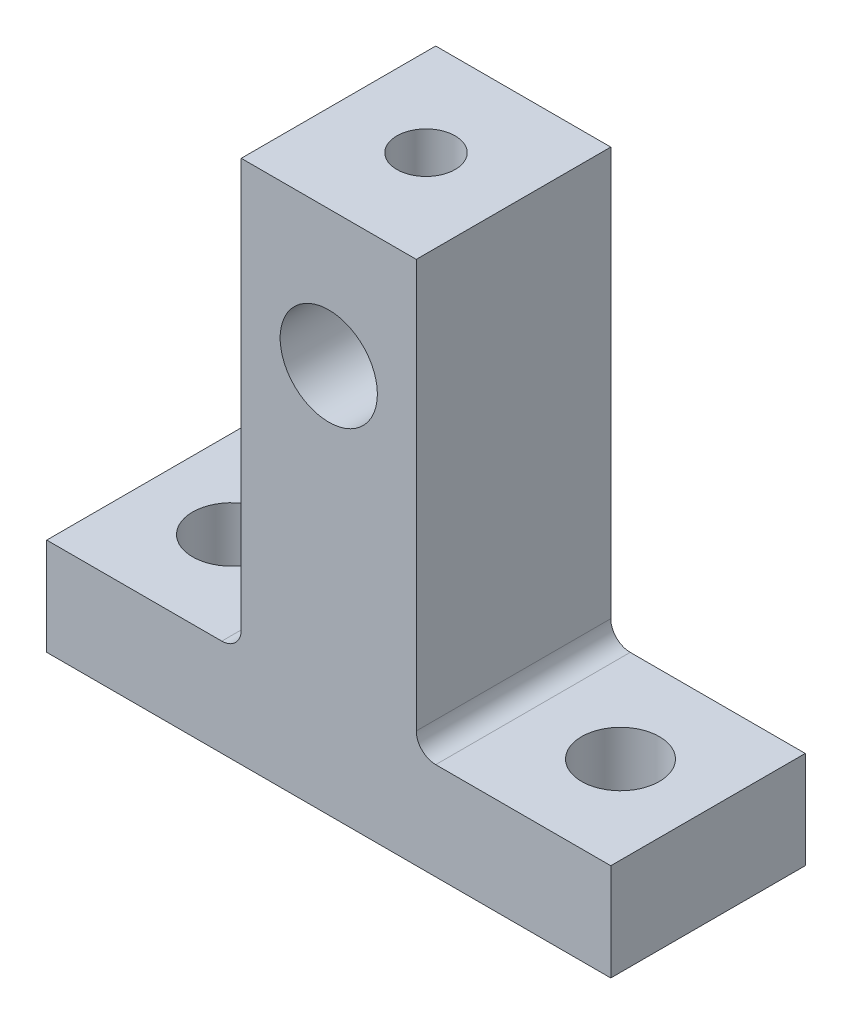
SolidWorks part; units mm, degrees
ref_plane "Front Plane" through (0, 0, 0) normal (0, 0, 1) x (1, 0, 0)
ref_plane "Top Plane" through (0, 0, 0) normal (0, 1, 0) x (1, 0, 0)
ref_plane "Right Plane" through (0, 0, 0) normal (1, 0, 0) x (0, 0, -1)
sketch "Sketch1" plane through (0, 0, 0) normal (0, 0, 1) x (1, 0, 0)
  line L0 (0, 0) -> (29, 0)
  line L1 (29, 0) -> (29, 5)
  line L2 (29, 5) -> (20, 5)
  line L3 (19, 6) -> (19, 27)
  line L4 (19, 27) -> (10, 27)
  line L5 (10, 27) -> (10, 6)
  line L6 (9, 5) -> (0, 5)
  line L7 (0, 5) -> (0, 0)
  line L8 (14.5, 27) -> (14.5, -4.2404) construction
  circle A0 centre (14.5, 20) radius 2.5
  arc A1 (20, 5) -> (19, 6) centre (20, 6) cw
  arc A2 (10, 6) -> (9, 5) centre (9, 6) cw
  point P13 (0, 0)
  point P18 (10, 5)
  dimension "D6" = 5
  dimension "D8" = 1
  dimension "D1" = 29
  dimension "D2" = 27
  dimension "D3" = 5
  dimension "D4" = 5
  dimension "D5" = 10
  dimension "D7" = 7
extrude "Boss-Extrude1" add sketch "Sketch1" along normal mid plane 10
sketch "Sketch2" plane through (0, 27, 0) normal (0, 1, 0) x (1, 0, 0)
  line L0 (14.5, 5) -> (14.5, -5) construction
  line L1 (19, 5) -> (10, 5) construction
  line L2 (19, -5) -> (10, -5) construction
  circle A0 centre (14.5, 0) radius 1.5
  point P8 (0, 0)
  dimension "D1" = 3
extrude "Cut-Extrude1" cut sketch "Sketch2" against normal up to surface (4.5 mm away)
sketch "Sketch3" plane through (0, 5, 0) normal (0, 1, 0) x (1, 0, 0)
  line L0 (14.5, -5) -> (14.5, 5) construction
  circle A0 centre (4.5, 0) radius 2
  circle A1 centre (24.5, 0) radius 2
  circle A2 centre (14.5, 0) radius 1.5 construction
  dimension "D1" = 4
  dimension "D2" = 10
  dimension "D3" = 10
extrude "Cut-Extrude2" cut sketch "Sketch3" against normal through all
